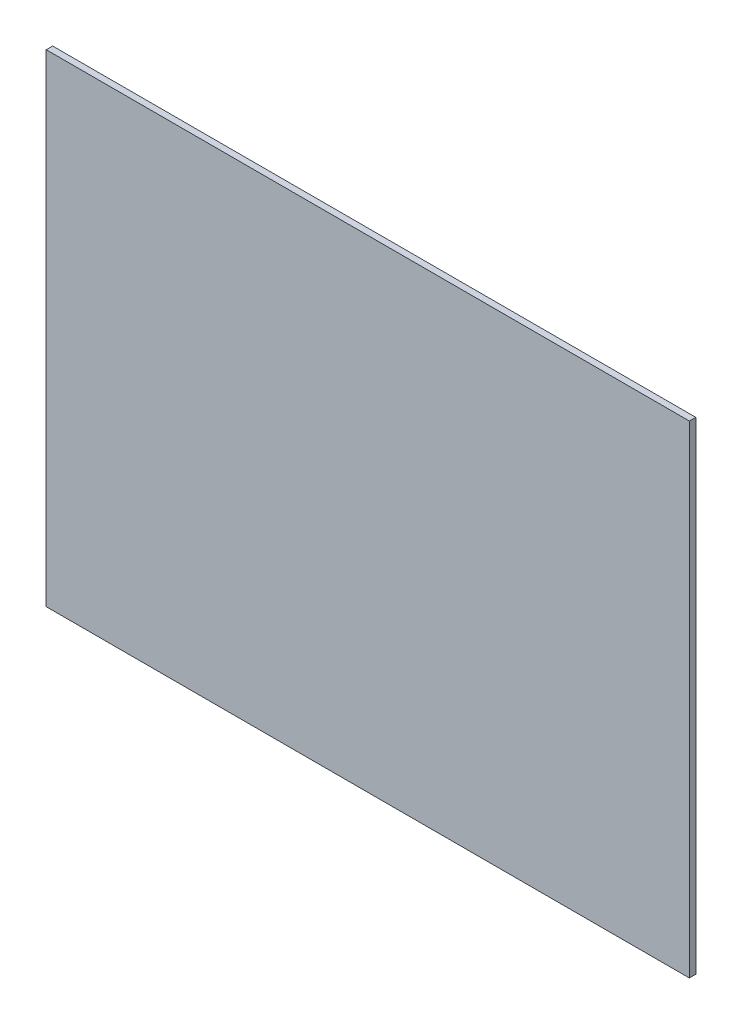
SolidWorks part; units mm, degrees
ref_plane "Front Plane" through (0, 0, 0) normal (0, 0, 1) x (1, 0, 0)
ref_plane "Top Plane" through (0, 0, 0) normal (0, 1, 0) x (1, 0, 0)
ref_plane "Right Plane" through (0, 0, 0) normal (1, 0, 0) x (0, 0, -1)
sketch "Sketch1" plane through (0, 0, 0) normal (0, 0, 1) x (1, 0, 0)
  line L0 (0, 0) -> (200, 0)
  line L1 (200, 0) -> (200, 150)
  line L2 (200, 150) -> (0, 150)
  line L3 (0, 150) -> (0, 0)
  dimension "D1" = 200
  dimension "D2" = 150
extrude "Boss-Extrude1" add sketch "Sketch1" along normal blind 2
